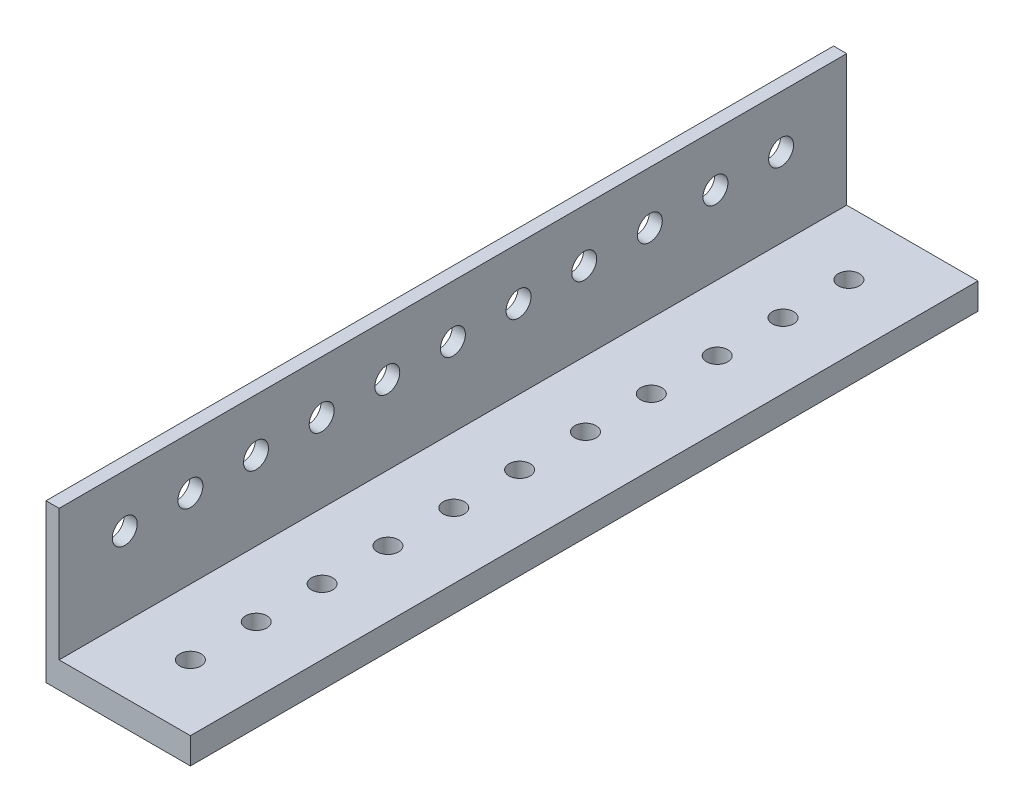
SolidWorks part; units mm, degrees
ref_plane "Front Plane" through (0, 0, 0) normal (0, 0, 1) x (1, 0, 0)
ref_plane "Top Plane" through (0, 0, 0) normal (0, 1, 0) x (1, 0, 0)
ref_plane "Right Plane" through (0, 0, 0) normal (1, 0, 0) x (0, 0, -1)
sketch "Sketch1" plane through (0, 0, 0) normal (1, 0, 0) x (0, 0, -1)
  line L0 (1.495, 4.8503) -> (1.495, -15.4697) construction
  line L1 (-11.205, 15.0103) -> (141.195, 15.0103)
  line L2 (-11.205, 15.0103) -> (-11.205, -15.4697)
  line L3 (-11.205, -15.4697) -> (141.195, -15.4697)
  line L4 (141.195, 15.0103) -> (141.195, -15.4697)
  line L5 (1.495, 4.8503) -> (-11.205, 4.8503) construction
  circle A0 centre (1.495, 4.8503) radius 2.413
  circle A1 centre (14.195, 4.8503) radius 2.413
  circle A2 centre (26.895, 4.8503) radius 2.413
  circle A3 centre (39.595, 4.8503) radius 2.413
  circle A4 centre (52.295, 4.8503) radius 2.413
  circle A5 centre (64.995, 4.8503) radius 2.413
  circle A6 centre (77.695, 4.8503) radius 2.413
  circle A7 centre (90.395, 4.8503) radius 2.413
  circle A8 centre (103.095, 4.8503) radius 2.413
  circle A9 centre (115.795, 4.8503) radius 2.413
  circle A10 centre (128.495, 4.8503) radius 2.413
  dimension "D3" = 4.826
  dimension "D4" = 20.32
  dimension "D5" = 12.7
  dimension "D1" = 30.48
  dimension "D2" = 152.4
  dimension "D6" = 11
extrude "Boss-Extrude1" add sketch "Sketch1" along normal blind 2.54
sketch "Sketch2" plane through (2.54, 0, 0) normal (1, 0, 0) x (0, 0, -1)
  line L0 (141.195, -15.4697) -> (141.195, 15.0103) construction
  line L1 (-11.205, -15.4697) -> (141.195, -15.4697)
  line L2 (-11.205, -15.4697) -> (-11.205, -10.3897)
  line L3 (-11.205, -10.3897) -> (141.195, -10.3897)
  line L4 (141.195, -15.4697) -> (141.195, -10.3897)
  dimension "D1" = 5.08
extrude "Boss-Extrude2" add sketch "Sketch2" along normal blind 25.4
sketch "Sketch3" plane through (0, -10.3897, 0) normal (0, 1, 0) x (1, 0, 0)
  line L0 (15.24, 1.495) -> (27.94, 1.495) construction
  line L1 (15.24, 128.9064) -> (15.24, 141.195) construction
  line L2 (15.24, 1.495) -> (15.24, -11.205) construction
  line L3 (27.94, -11.205) -> (2.54, -11.205) construction
  line L4 (27.94, 141.195) -> (27.94, -11.205) construction
  line L5 (27.94, 141.195) -> (2.54, 141.195) construction
  line L6 (15.24, 128.9064) -> (15.24, 116.1653) construction
  line L7 (15.24, 116.1653) -> (15.24, 103.4241) construction
  line L8 (15.24, 103.4241) -> (15.24, 90.683) construction
  line L9 (15.24, 90.683) -> (15.24, 77.9418) construction
  line L10 (15.24, 77.9418) -> (15.24, 65.2007) construction
  line L11 (15.24, 65.2007) -> (15.24, 52.4596) construction
  line L12 (15.24, 52.4596) -> (15.24, 39.7184) construction
  line L13 (15.24, 39.7184) -> (15.24, 26.9773) construction
  line L14 (15.24, 26.9773) -> (15.24, 14.2361) construction
  line L15 (15.24, 14.2361) -> (15.24, 1.495) construction
  circle A0 centre (15.24, 1.495) radius 2.0545
  circle A1 centre (15.24, 14.2361) radius 2.0545
  circle A2 centre (15.24, 26.9773) radius 2.0545
  circle A3 centre (15.24, 39.7184) radius 2.0545
  circle A4 centre (15.24, 52.4596) radius 2.0545
  circle A5 centre (15.24, 65.2007) radius 2.0545
  circle A6 centre (15.24, 77.9418) radius 2.0545
  circle A7 centre (15.24, 90.683) radius 2.0545
  circle A8 centre (15.24, 103.4241) radius 2.0545
  circle A9 centre (15.24, 116.1653) radius 2.0545
  circle A10 centre (15.24, 128.9064) radius 2.0545
  dimension "D1" = 12.7
  dimension "D2" = 12.7
extrude "Cut-Extrude1" cut sketch "Sketch3" against normal through all
